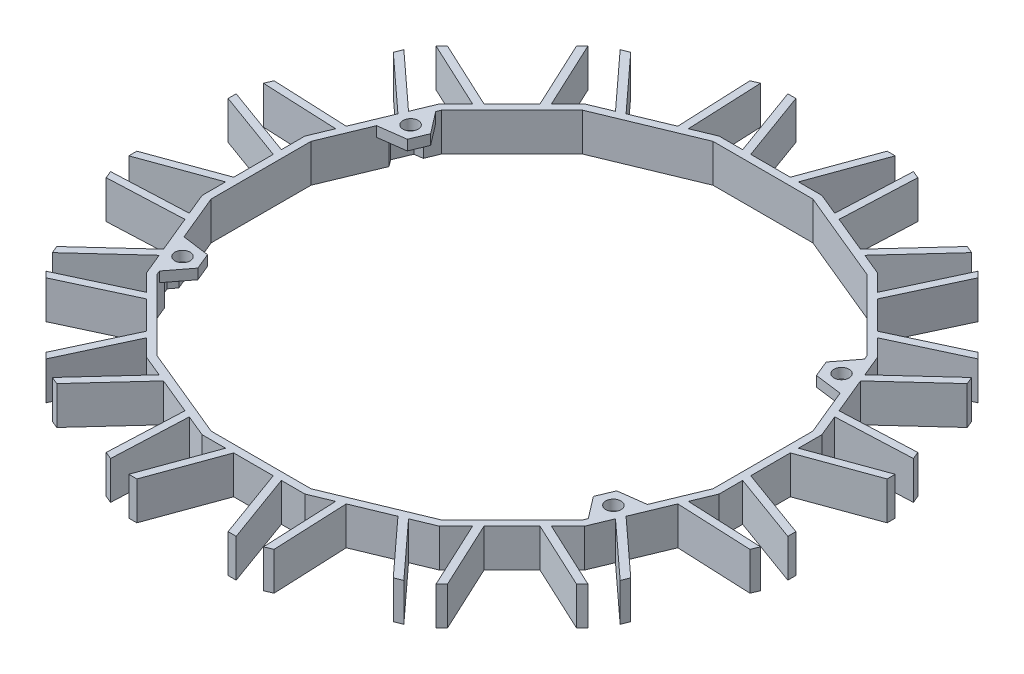
SolidWorks part; units mm, degrees
ref_plane "Front Plane" through (0, 0, 0) normal (0, 0, 1) x (1, 0, 0)
ref_plane "Top Plane" through (0, 0, 0) normal (0, 1, 0) x (1, 0, 0)
ref_plane "Right Plane" through (0, 0, 0) normal (1, 0, 0) x (0, 0, -1)
sketch "Sketch1" plane through (0, 0, 0) normal (0, 1, 0) x (1, 0, 0)
  line L1 (65, 12.9293) -> (55.1043, 36.8195)
  line L2 (55.1043, 36.8195) -> (36.8195, 55.1043)
  line L3 (36.8195, 55.1043) -> (12.9293, 65)
  line L4 (12.9293, 65) -> (-12.9293, 65)
  line L5 (-12.9293, 65) -> (-36.8195, 55.1043)
  line L6 (-36.8195, 55.1043) -> (-55.1043, 36.8195)
  line L7 (-55.1043, 36.8195) -> (-65, 12.9293)
  line L8 (-65, 12.9293) -> (-65, -12.9293)
  line L9 (-65, -12.9293) -> (-55.1043, -36.8195)
  line L10 (-55.1043, -36.8195) -> (-36.8195, -55.1043)
  line L11 (-36.8195, -55.1043) -> (-12.9293, -65)
  line L12 (-12.9293, -65) -> (12.9293, -65)
  line L13 (12.9293, -65) -> (36.8195, -55.1043)
  line L14 (36.8195, -55.1043) -> (55.1043, -36.8195)
  line L15 (55.1043, -36.8195) -> (65, -12.9293)
  line L16 (65, -12.9293) -> (65, 12.9293)
  circle A0 centre (0, 0) radius 65 construction
  dimension "D1" = 130
extrude "Boss-Extrude1" add sketch "Sketch1" along normal blind 1.6
sketch "Sketch2" plane through (0, 0, 0) normal (0, -1, 0) x (1, 0, 0)
  line L0 (-9, 65) -> (-3.9044, 51)
  line L1 (-12.9293, 65) -> (12.9293, 65) construction
  line L2 (-3.9044, 51) -> (3.9044, 51)
  line L3 (3.9044, 51) -> (9, 65)
  line L4 (9, 65) -> (10.5963, 65)
  line L5 (10.5963, 65) -> (4.9547, 49.5)
  line L6 (4.9547, 49.5) -> (-4.9547, 49.5)
  line L7 (-4.9547, 49.5) -> (-10.5963, 65)
  line L8 (-10.5963, 65) -> (-9, 65)
  line L131 (15.0847, 64.1072) -> (16.5595, 63.4963)
  line L132 (16.5595, 63.4963) -> (15.9096, 48.612)
  line L133 (15.9096, 48.612) -> (23.1241, 45.6237)
  line L134 (23.1241, 45.6237) -> (33.1893, 56.608)
  line L135 (33.1893, 56.608) -> (34.6641, 55.9972)
  line L136 (34.6641, 55.9972) -> (23.5204, 43.8359)
  line L137 (23.5204, 43.8359) -> (14.3653, 47.6281)
  line L138 (14.3653, 47.6281) -> (15.0847, 64.1072)
  line L139 (38.4692, 53.4546) -> (39.598, 52.3259)
  line L140 (39.598, 52.3259) -> (33.3016, 38.8233)
  line L141 (33.3016, 38.8233) -> (38.8233, 33.3016)
  line L142 (38.8233, 33.3016) -> (52.3259, 39.598)
  line L143 (52.3259, 39.598) -> (53.4546, 38.4692)
  line L144 (53.4546, 38.4692) -> (38.5053, 31.4983)
  line L145 (38.5053, 31.4983) -> (31.4983, 38.5053)
  line L146 (31.4983, 38.5053) -> (38.4692, 53.4546)
  line L147 (55.9972, 34.6641) -> (56.608, 33.1893)
  line L148 (56.608, 33.1893) -> (45.6237, 23.1241)
  line L149 (45.6237, 23.1241) -> (48.612, 15.9096)
  line L150 (48.612, 15.9096) -> (63.4963, 16.5595)
  line L151 (63.4963, 16.5595) -> (64.1072, 15.0847)
  line L152 (64.1072, 15.0847) -> (47.6281, 14.3653)
  line L153 (47.6281, 14.3653) -> (43.8359, 23.5204)
  line L154 (43.8359, 23.5204) -> (55.9972, 34.6641)
  line L155 (65, 10.5963) -> (65, 9)
  line L156 (65, 9) -> (51, 3.9044)
  line L157 (51, 3.9044) -> (51, -3.9044)
  line L158 (51, -3.9044) -> (65, -9)
  line L167 (65, -9) -> (65, -10.5963)
  line L184 (65, -10.5963) -> (49.5, -4.9547)
  line L185 (49.5, -4.9547) -> (49.5, 4.9547)
  line L186 (49.5, 4.9547) -> (65, 10.5963)
  line L187 (64.1072, -15.0847) -> (63.4963, -16.5595)
  line L188 (63.4963, -16.5595) -> (48.612, -15.9096)
  line L189 (48.612, -15.9096) -> (45.6237, -23.1241)
  line L190 (45.6237, -23.1241) -> (56.608, -33.1893)
  line L191 (56.608, -33.1893) -> (55.9972, -34.6641)
  line L192 (55.9972, -34.6641) -> (43.8359, -23.5204)
  line L193 (43.8359, -23.5204) -> (47.6281, -14.3653)
  line L194 (47.6281, -14.3653) -> (64.1072, -15.0847)
  line L195 (53.4546, -38.4692) -> (52.3259, -39.598)
  line L196 (52.3259, -39.598) -> (38.8233, -33.3016)
  line L197 (38.8233, -33.3016) -> (33.3016, -38.8233)
  line L198 (33.3016, -38.8233) -> (39.598, -52.3259)
  line L199 (39.598, -52.3259) -> (38.4692, -53.4546)
  line L200 (38.4692, -53.4546) -> (31.4983, -38.5053)
  line L201 (31.4983, -38.5053) -> (38.5053, -31.4983)
  line L202 (38.5053, -31.4983) -> (53.4546, -38.4692)
  line L203 (34.6641, -55.9972) -> (33.1893, -56.608)
  line L204 (33.1893, -56.608) -> (23.1241, -45.6237)
  line L205 (23.1241, -45.6237) -> (15.9096, -48.612)
  line L206 (15.9096, -48.612) -> (16.5595, -63.4963)
  line L207 (16.5595, -63.4963) -> (15.0847, -64.1072)
  line L208 (15.0847, -64.1072) -> (14.3653, -47.6281)
  line L209 (14.3653, -47.6281) -> (23.5204, -43.8359)
  line L210 (23.5204, -43.8359) -> (34.6641, -55.9972)
  line L211 (10.5963, -65) -> (9, -65)
  line L212 (9, -65) -> (3.9044, -51)
  line L213 (3.9044, -51) -> (-3.9044, -51)
  line L214 (-3.9044, -51) -> (-9, -65)
  line L215 (-9, -65) -> (-10.5963, -65)
  line L216 (-10.5963, -65) -> (-4.9547, -49.5)
  line L217 (-4.9547, -49.5) -> (4.9547, -49.5)
  line L218 (4.9547, -49.5) -> (10.5963, -65)
  line L219 (-15.0847, -64.1072) -> (-16.5595, -63.4963)
  line L220 (-16.5595, -63.4963) -> (-15.9096, -48.612)
  line L221 (-15.9096, -48.612) -> (-23.1241, -45.6237)
  line L222 (-23.1241, -45.6237) -> (-33.1893, -56.608)
  line L223 (-33.1893, -56.608) -> (-34.6641, -55.9972)
  line L224 (-34.6641, -55.9972) -> (-23.5204, -43.8359)
  line L225 (-23.5204, -43.8359) -> (-14.3653, -47.6281)
  line L226 (-14.3653, -47.6281) -> (-15.0847, -64.1072)
  line L227 (-38.4692, -53.4546) -> (-39.598, -52.3259)
  line L228 (-39.598, -52.3259) -> (-33.3016, -38.8233)
  line L229 (-33.3016, -38.8233) -> (-38.8233, -33.3016)
  line L230 (-38.8233, -33.3016) -> (-52.3259, -39.598)
  line L231 (-52.3259, -39.598) -> (-53.4546, -38.4692)
  line L232 (-53.4546, -38.4692) -> (-38.5053, -31.4983)
  line L233 (-38.5053, -31.4983) -> (-31.4983, -38.5053)
  line L234 (-31.4983, -38.5053) -> (-38.4692, -53.4546)
  line L235 (-55.9972, -34.6641) -> (-56.608, -33.1893)
  line L236 (-56.608, -33.1893) -> (-45.6237, -23.1241)
  line L237 (-45.6237, -23.1241) -> (-48.612, -15.9096)
  line L238 (-48.612, -15.9096) -> (-63.4963, -16.5595)
  line L239 (-63.4963, -16.5595) -> (-64.1072, -15.0847)
  line L240 (-64.1072, -15.0847) -> (-47.6281, -14.3653)
  line L241 (-47.6281, -14.3653) -> (-43.8359, -23.5204)
  line L242 (-43.8359, -23.5204) -> (-55.9972, -34.6641)
  line L243 (-65, -10.5963) -> (-65, -9)
  line L244 (-65, -9) -> (-51, -3.9044)
  line L245 (-51, -3.9044) -> (-51, 3.9044)
  line L246 (-51, 3.9044) -> (-65, 9)
  line L247 (-65, 9) -> (-65, 10.5963)
  line L248 (-65, 10.5963) -> (-49.5, 4.9547)
  line L249 (-49.5, 4.9547) -> (-49.5, -4.9547)
  line L250 (-49.5, -4.9547) -> (-65, -10.5963)
  line L251 (-64.1072, 15.0847) -> (-63.4963, 16.5595)
  line L252 (-63.4963, 16.5595) -> (-48.612, 15.9096)
  line L253 (-48.612, 15.9096) -> (-45.6237, 23.1241)
  line L254 (-45.6237, 23.1241) -> (-56.608, 33.1893)
  line L255 (-56.608, 33.1893) -> (-55.9972, 34.6641)
  line L256 (-55.9972, 34.6641) -> (-43.8359, 23.5204)
  line L257 (-43.8359, 23.5204) -> (-47.6281, 14.3653)
  line L258 (-47.6281, 14.3653) -> (-64.1072, 15.0847)
  line L259 (-53.4546, 38.4692) -> (-52.3259, 39.598)
  line L260 (-52.3259, 39.598) -> (-38.8233, 33.3016)
  line L261 (-38.8233, 33.3016) -> (-33.3016, 38.8233)
  line L262 (-33.3016, 38.8233) -> (-39.598, 52.3259)
  line L263 (-39.598, 52.3259) -> (-38.4692, 53.4546)
  line L264 (-38.4692, 53.4546) -> (-31.4983, 38.5053)
  line L265 (-31.4983, 38.5053) -> (-38.5053, 31.4983)
  line L266 (-38.5053, 31.4983) -> (-53.4546, 38.4692)
  line L267 (-34.6641, 55.9972) -> (-33.1893, 56.608)
  line L268 (-33.1893, 56.608) -> (-23.1241, 45.6237)
  line L269 (-23.1241, 45.6237) -> (-15.9096, 48.612)
  line L270 (-15.9096, 48.612) -> (-16.5595, 63.4963)
  line L271 (-16.5595, 63.4963) -> (-15.0847, 64.1072)
  line L272 (-15.0847, 64.1072) -> (-14.3653, 47.6281)
  line L273 (-14.3653, 47.6281) -> (-23.5204, 43.8359)
  line L274 (-23.5204, 43.8359) -> (-34.6641, 55.9972)
  point P4 (0, 51)
  point P11 (0, 49.5)
  point P136 (0, 0)
  point P138 (0, 0)
  dimension "D6" = 16
  dimension "D1" = 1.5
  dimension "D2" = 1.5
  dimension "D3" = 18
  dimension "D4" = 40
  dimension "D5" = 14
extrude "Boss-Extrude5" add sketch "Sketch2" along normal blind 7.5
sketch "Sketch6" plane through (0, 1.6, 0) normal (0, 1, 0) x (1, 0, 0)
  line L1 (-42.5, -22.5) -> (42.5, -22.5) construction
  line L2 (-42.5, -22.5) -> (-42.5, 22.5) construction
  line L3 (-42.5, 22.5) -> (42.5, 22.5) construction
  line L4 (42.5, -22.5) -> (42.5, 22.5) construction
  line L5 (-42.5, -22.5) -> (42.5, 22.5) construction
  line L6 (-42.5, 22.5) -> (42.5, -22.5) construction
  circle A0 centre (-42.5, 22.5) radius 1.5
  circle A1 centre (-42.5, -22.5) radius 1.5
  circle A2 centre (42.5, -22.5) radius 1.5
  circle A3 centre (42.5, 22.5) radius 1.5
  point P0 (0, 0)
  dimension "D3" = 3
  dimension "D1" = 85
  dimension "D2" = 45
extrude "Cut-Extrude2" cut sketch "Sketch6" against normal up to surface (1.6 mm away) up to face at (0, 0, 0)
sketch "Sketch17" plane through (0, -7.5, 0) normal (0, -1, 0) x (1, 0, 0)
  line L1 (-9.8462, 49.5) -> (-28.0395, 41.9641)
  line L2 (-28.0395, 41.9641) -> (-41.9641, 28.0395)
  line L3 (-41.9641, 28.0395) -> (-49.5, 9.8462)
  line L4 (-49.5, 9.8462) -> (-49.5, -9.8462)
  line L5 (-49.5, -9.8462) -> (-41.9641, -28.0395)
  line L6 (-41.9641, -28.0395) -> (-28.0395, -41.9641)
  line L7 (-28.0395, -41.9641) -> (-9.8462, -49.5)
  line L8 (-9.8462, -49.5) -> (9.8462, -49.5)
  line L9 (9.8462, -49.5) -> (28.0395, -41.9641)
  line L10 (28.0395, -41.9641) -> (41.9641, -28.0395)
  line L11 (41.9641, -28.0395) -> (49.5, -9.8462)
  line L12 (49.5, -9.8462) -> (49.5, 9.8462)
  line L13 (49.5, 9.8462) -> (41.9641, 28.0395)
  line L14 (41.9641, 28.0395) -> (28.0395, 41.9641)
  line L15 (28.0395, 41.9641) -> (9.8462, 49.5)
  line L16 (9.8462, 49.5) -> (-9.8462, 49.5)
  line L18 (-49.5, -4.9547) -> (-49.5, 4.9547) construction
  line L20 (-10.1445, 51) -> (-28.8892, 43.2357)
  line L21 (-28.8892, 43.2357) -> (-43.2357, 28.8892)
  line L22 (-43.2357, 28.8892) -> (-51, 10.1445)
  line L23 (-51, 10.1445) -> (-51, -10.1445)
  line L24 (-51, -10.1445) -> (-43.2357, -28.8892)
  line L25 (-43.2357, -28.8892) -> (-28.8892, -43.2357)
  line L26 (-28.8892, -43.2357) -> (-10.1445, -51)
  line L27 (-10.1445, -51) -> (10.1445, -51)
  line L28 (10.1445, -51) -> (28.8892, -43.2357)
  line L29 (28.8892, -43.2357) -> (43.2357, -28.8892)
  line L30 (43.2357, -28.8892) -> (51, -10.1445)
  line L31 (51, -10.1445) -> (51, 10.1445)
  line L32 (51, 10.1445) -> (43.2357, 28.8892)
  line L33 (43.2357, 28.8892) -> (28.8892, 43.2357)
  line L34 (28.8892, 43.2357) -> (10.1445, 51)
  line L35 (10.1445, 51) -> (-10.1445, 51)
  line L36 (-51, 3.9044) -> (-51, -3.9044) construction
  circle A0 centre (0, 0) radius 49.5 construction
  circle A1 centre (0, 0) radius 51 construction
extrude "Boss-Extrude9" add sketch "Sketch17" against normal up to surface (7.5 mm away) up to face at (-58, 0, 0)
sketch "Sketch16" plane through (0, -7.5, 0) normal (0, -1, 0) x (1, 0, 0)
  line L0 (-49.5, 9.8462) -> (-41.9641, 28.0395) construction
  line L1 (-43.8477, 19.2462) -> (-40.356, 19.7059)
  line L2 (-40.356, 19.7059) -> (-39.0083, 22.9597)
  line L3 (-39.0083, 22.9597) -> (-41.1523, 25.7538)
  line L4 (-41.1523, 25.7538) -> (-44.644, 25.2941)
  line L5 (-44.644, 25.2941) -> (-45.9917, 22.0403)
  line L6 (-45.9917, 22.0403) -> (-43.8477, 19.2462)
  line L7 (0, -0.88) -> (0, 0.88) construction
  line L8 (45.9917, 22.0403) -> (43.8477, 19.2462)
  line L9 (44.644, 25.2941) -> (45.9917, 22.0403)
  line L10 (41.1523, 25.7538) -> (44.644, 25.2941)
  line L11 (39.0083, 22.9597) -> (41.1523, 25.7538)
  line L12 (40.356, 19.7059) -> (39.0083, 22.9597)
  line L13 (43.8477, 19.2462) -> (40.356, 19.7059)
  line L14 (0.88, 0) -> (-0.88, 0) construction
  line L15 (44.644, -25.2941) -> (45.9917, -22.0403)
  line L16 (41.1523, -25.7538) -> (44.644, -25.2941)
  line L17 (39.0083, -22.9597) -> (41.1523, -25.7538)
  line L18 (40.356, -19.7059) -> (39.0083, -22.9597)
  line L19 (43.8477, -19.2462) -> (40.356, -19.7059)
  line L20 (45.9917, -22.0403) -> (43.8477, -19.2462)
  line L21 (-45.9917, -22.0403) -> (-43.8477, -19.2462)
  line L22 (-44.644, -25.2941) -> (-45.9917, -22.0403)
  line L23 (-41.1523, -25.7538) -> (-44.644, -25.2941)
  line L24 (-39.0083, -22.9597) -> (-41.1523, -25.7538)
  line L25 (-40.356, -19.7059) -> (-39.0083, -22.9597)
  line L26 (-43.8477, -19.2462) -> (-40.356, -19.7059)
  circle A0 centre (-42.5, 22.5) radius 3.05 construction
  dimension "D1" = 6.1
extrude "Cut-Extrude5" cut sketch "Sketch16" against normal up to surface (7.5 mm away) up to face at (42.5, 0, -21)
sketch "Sketch22" plane through (0, 0, 0) normal (0, -1, 0) x (1, 0, 0)
  line L0 (45.9917, 22.0403) -> (44.644, 25.2941) construction
  line L1 (44.644, 25.2941) -> (41.1523, 25.7538)
  line L2 (41.1523, 25.7538) -> (39.0083, 22.9597)
  line L3 (39.0083, 22.9597) -> (40.356, 19.7059)
  line L4 (40.356, 19.7059) -> (43.8477, 19.2462)
  line L5 (43.8477, 19.2462) -> (45.9917, 22.0403)
  line L6 (45.9917, 22.0403) -> (44.644, 25.2941)
  line L7 (0, -0.88) -> (0, 0.88) construction
  line L8 (-45.9917, 22.0403) -> (-44.644, 25.2941)
  line L9 (-43.8477, 19.2462) -> (-45.9917, 22.0403)
  line L10 (-40.356, 19.7059) -> (-43.8477, 19.2462)
  line L11 (-39.0083, 22.9597) -> (-40.356, 19.7059)
  line L12 (-41.1523, 25.7538) -> (-39.0083, 22.9597)
  line L13 (-44.644, 25.2941) -> (-41.1523, 25.7538)
  line L14 (0.88, 0) -> (-0.88, 0) construction
  line L15 (-44.644, -25.2941) -> (-41.1523, -25.7538)
  line L16 (-41.1523, -25.7538) -> (-39.0083, -22.9597)
  line L17 (-39.0083, -22.9597) -> (-40.356, -19.7059)
  line L18 (-40.356, -19.7059) -> (-43.8477, -19.2462)
  line L19 (-43.8477, -19.2462) -> (-45.9917, -22.0403)
  line L20 (-45.9917, -22.0403) -> (-44.644, -25.2941)
  line L21 (45.9917, -22.0403) -> (44.644, -25.2941)
  line L22 (43.8477, -19.2462) -> (45.9917, -22.0403)
  line L23 (40.356, -19.7059) -> (43.8477, -19.2462)
  line L24 (39.0083, -22.9597) -> (40.356, -19.7059)
  line L25 (41.1523, -25.7538) -> (39.0083, -22.9597)
  line L26 (44.644, -25.2941) -> (41.1523, -25.7538)
  circle A0 centre (42.5, 22.5) radius 3.05 construction
  circle A1 centre (42.5, 22.5) radius 1.5
  circle A2 centre (42.5, 22.5) radius 1.5 construction
  circle A3 centre (42.5, -22.5) radius 3.05 construction
  circle A4 centre (42.5, -22.5) radius 1.5
  circle A5 centre (-42.5, 22.5) radius 1.5
  circle A6 centre (-42.5, -22.5) radius 1.5
extrude "Boss-Extrude12" add sketch "Sketch22" along normal blind 2
sketch "Sketch23" plane through (0, -2, 0) normal (0, -1, 0) x (1, 0, 0)
  line L0 (-41.1523, 25.7538) -> (-42.2943, 27.2422)
  line L1 (-43.0123, 25.5089) -> (-41.9641, 28.0395) construction
  line L2 (-43.8477, 19.2462) -> (-45.7078, 19.0014)
  line L3 (-49.5, 9.8462) -> (-44.9898, 20.7347) construction
  line L4 (-43.8477, 19.2462) -> (-40.356, 19.7059) construction
  line L5 (-39.0083, 22.9597) -> (-41.1523, 25.7538) construction
  line L6 (-42.2943, 27.2422) -> (-43.0123, 25.5089)
  line L7 (-43.0123, 25.5089) -> (-41.1523, 25.7538)
  line L8 (-44.9898, 20.7347) -> (-43.8477, 19.2462)
  line L9 (-45.7078, 19.0014) -> (-44.9898, 20.7347)
  line L10 (0.88, 0) -> (-0.88, 0) construction
  line L11 (-43.8477, -19.2462) -> (-45.7078, -19.0014)
  line L12 (-44.9898, -20.7347) -> (-43.8477, -19.2462)
  line L13 (-45.7078, -19.0014) -> (-44.9898, -20.7347)
  line L14 (-42.2943, -27.2422) -> (-43.0123, -25.5089)
  line L15 (-41.1523, -25.7538) -> (-42.2943, -27.2422)
  line L16 (-43.0123, -25.5089) -> (-41.1523, -25.7538)
  line L17 (0, -0.88) -> (0, 0.88) construction
  line L18 (43.0123, -25.5089) -> (41.1523, -25.7538)
  line L19 (41.1523, -25.7538) -> (42.2943, -27.2422)
  line L20 (42.2943, -27.2422) -> (43.0123, -25.5089)
  line L21 (45.7078, -19.0014) -> (44.9898, -20.7347)
  line L22 (44.9898, -20.7347) -> (43.8477, -19.2462)
  line L23 (43.8477, -19.2462) -> (45.7078, -19.0014)
  line L24 (45.7078, 19.0014) -> (44.9898, 20.7347)
  line L25 (44.9898, 20.7347) -> (43.8477, 19.2462)
  line L26 (43.0123, 25.5089) -> (41.1523, 25.7538)
  line L27 (42.2943, 27.2422) -> (43.0123, 25.5089)
  line L28 (43.8477, 19.2462) -> (45.7078, 19.0014)
  line L29 (41.1523, 25.7538) -> (42.2943, 27.2422)
extrude "Boss-Extrude13" add sketch "Sketch23" against normal up to surface (2 mm away) up to face at (11.4484, 0, 57.555)
sketch "Sketch18" plane through (0, 1.6, 0) normal (0, 1, 0) x (1, 0, 0)
  line L0 (-65, 12.9293) -> (-65, -12.9293) construction
  line L1 (-36.8195, 55.1043) -> (-55.1043, 36.8195)
  line L2 (-55.1043, 36.8195) -> (-65, 12.9293)
  line L3 (-65, 12.9293) -> (-65, -12.9293)
  line L4 (-65, -12.9293) -> (-55.1043, -36.8195)
  line L5 (-55.1043, -36.8195) -> (-36.8195, -55.1043)
  line L6 (-36.8195, -55.1043) -> (-12.9293, -65)
  line L7 (-12.9293, -65) -> (12.9293, -65)
  line L8 (12.9293, -65) -> (36.8195, -55.1043)
  line L9 (36.8195, -55.1043) -> (55.1043, -36.8195)
  line L10 (55.1043, -36.8195) -> (65, -12.9293)
  line L11 (65, -12.9293) -> (65, 12.9293)
  line L12 (65, 12.9293) -> (55.1043, 36.8195)
  line L13 (55.1043, 36.8195) -> (36.8195, 55.1043)
  line L14 (36.8195, 55.1043) -> (12.9293, 65)
  line L15 (12.9293, 65) -> (-12.9293, 65)
  line L16 (-12.9293, 65) -> (-36.8195, 55.1043)
  circle A0 centre (0, 0) radius 65 construction
extrude "Cut-Extrude6" cut sketch "Sketch18" against normal up to surface (1.6 mm away) up to face at (11.4484, 0, 57.555)
